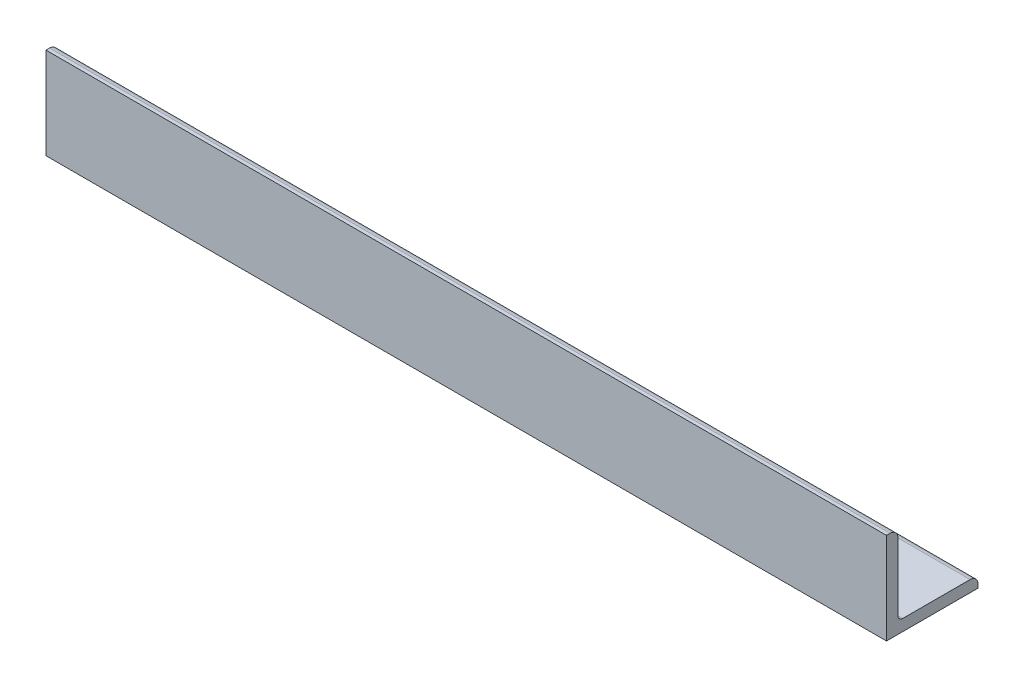
SolidWorks part; units mm, degrees
material "Liga 1060"
ref_plane "Plano frontal" through (0, 0, 0) normal (0, 0, 1) x (1, 0, 0)
ref_plane "Plano superior" through (0, 0, 0) normal (0, 1, 0) x (1, 0, 0)
ref_plane "Plano direito" through (0, 0, 0) normal (1, 0, 0) x (0, 0, -1)
sketch "Esboço1" plane through (0, 0, 0) normal (0, 1, 0) x (1, 0, 0)
  line L0 (-175, 0) -> (175, 0)
  point P3 (0, 0)
  dimension "D1" = 350
other "Aço cantoneira laminada 1020 3-16X1-1-2(1)"
ref_plane "Plano1" through (-175, 0, 0) normal (1, 0, 0) x (0, 0, -1)
sketch "Sketch11" plane through (-175, 0, 0) normal (1, 0, 0) x (0, 0, -1)
  line L0 (0, 0) -> (0, 38.1)
  line L1 (0, 38.1) -> (1.5, 38.1)
  line L2 (4.7625, 34.8375) -> (4.7625, 6.7625)
  line L3 (6.7625, 4.7625) -> (34.8375, 4.7625)
  line L4 (38.1, 1.5) -> (38.1, 0)
  line L5 (38.1, 0) -> (0, 0)
  line L6 (0, 38.1) -> (38.1, 0) construction
  line L7 (3.8069, 37.1444) -> (37.1444, 3.8069) construction
  arc A0 (38.1, 1.5) -> (34.8375, 4.7625) centre (34.8375, 1.5) ccw
  arc A1 (1.5, 38.1) -> (4.7625, 34.8375) centre (1.5, 34.8375) cw
  arc A2 (6.7625, 4.7625) -> (4.7625, 6.7625) centre (6.7625, 6.7625) cw
  point P10 (19.05, 0)
  point P14 (0, 19.05)
  point P15 (4.7625, 19.05)
  point P16 (19.05, 4.7625)
  point P17 (4.7625, 38.1)
  point P18 (38.1, 4.7625)
  point P19 (4.7625, 4.7625)
  point P20 (38.1, 38.1)
  point P23 (20.4757, 20.4757)
  point P24 (19.05, 19.05)
  point P25 (0, 0)
  dimension "D2" = 1.5
  dimension "Radius_1" = 2
  dimension "D1" = 4.7625
  dimension "H_leg" = 38.1
sketch "Esboço4" plane through (0, 0, 0) normal (0, 1, 0) x (1, 0, 0)
  line L0 (0, 0) -> (0, 19.76) construction
  line L1 (0, 19.76) -> (-87.5, 19.76) construction
  line L2 (0, 12) -> (0, 26.1) construction
  line L3 (-5, 12) -> (-5, 26.1)
  line L4 (5, 12) -> (5, 26.1)
  line L5 (175, 38.1) -> (-175, 38.1) construction
  line L6 (-175, 0) -> (175, 0) construction
  circle A0 centre (-87.5, 19.76) radius 4
  circle A1 centre (87.5, 19.76) radius 4
  arc A2 (-5, 12) -> (5, 12) centre (0, 12) ccw
  arc A3 (5, 26.1) -> (-5, 26.1) centre (0, 26.1) ccw
  point P9 (0, 19.05)
  dimension "D1" = 8
  dimension "D2" = 175
  dimension "D6" = 12
  dimension "D3" = 19.76
  dimension "D4" = 10
  dimension "D5" = 12
extrude "Corte-extrusão1" cut sketch "Esboço4" along normal through all
